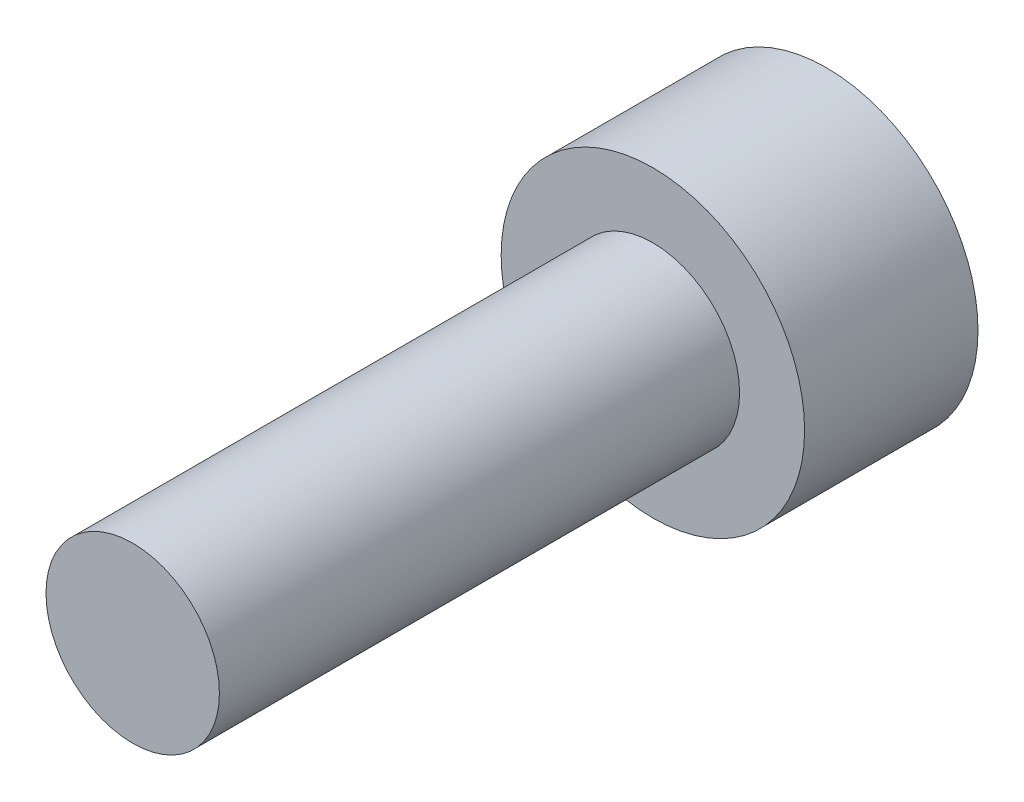
SolidWorks part; units mm, degrees
material "AISI 4340 Steel, normalized"
ref_plane "Front Plane" through (0, 0, 0) normal (0, 0, 1) x (1, 0, 0)
ref_plane "Top Plane" through (0, 0, 0) normal (0, 1, 0) x (1, 0, 0)
ref_plane "Right Plane" through (0, 0, 0) normal (1, 0, 0) x (0, 0, -1)
sketch "Sketch1" plane through (0, 0, 0) normal (0, 0, 1) x (1, 0, 0)
  circle A0 centre (0, 0) radius 3.5
extrude "Head_Envelope" add sketch "Sketch1" along normal blind 4 from offset 4
sketch "Sketch2" plane through (0, 0, 0) normal (0, 0, 1) x (1, 0, 0)
  circle A0 centre (0, 0) radius 2
extrude "Thread_Major_Envelope" add sketch "Sketch2" along normal blind 12
